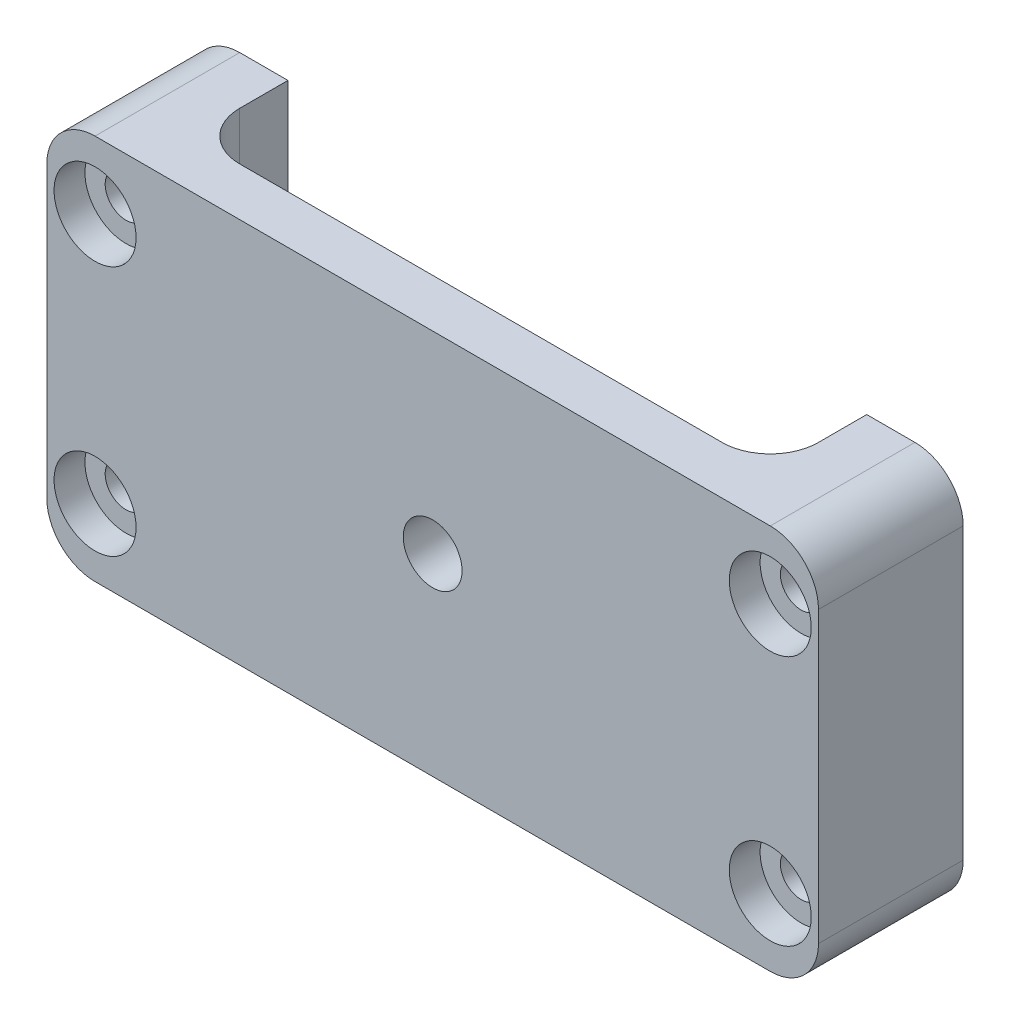
SolidWorks part; units mm, degrees
material "ABS"
ref_plane "Front Plane" through (0, 0, 0) normal (0, 0, 1) x (1, 0, 0)
ref_plane "Top Plane" through (0, 0, 0) normal (0, 1, 0) x (1, 0, 0)
ref_plane "Right Plane" through (0, 0, 0) normal (1, 0, 0) x (0, 0, -1)
sketch "Sketch1" plane through (0, 0, 0) normal (0, 0, 1) x (1, 0, 0)
  line L1 (0, 0) -> (40, 0)
  line L2 (0, 0) -> (0, 40)
  line L3 (0, 40) -> (40, 40)
  line L4 (40, 0) -> (40, 40)
  dimension "D1" = 40
  dimension "D2" = 40
extrude "Boss-Extrude1" add sketch "Sketch1" along normal blind 15
sketch "Sketch2" plane through (0, 0, 0) normal (0, -1, 0) x (1, 0, 0)
  line L1 (0, 0) -> (30, 0)
  line L2 (0, 0) -> (0, 10)
  line L3 (0, 10) -> (30, 10)
  line L4 (30, 0) -> (30, 10)
  dimension "D1" = 30
  dimension "D2" = 10
extrude "Cut-Extrude1" cut sketch "Sketch2" against normal through all
fillet "Fillet1" radius 5 1 edges at (30, 20, 10)
fillet "Fillet2" radius 5 2 edges at (40, 40, 7.5) (40, 0, 7.5)
hole_wizard "CBORE for M4 Pan Head Machine Screw1" positions "3DSketch1" profile "Sketch3" counterbore size "M4" standard "ANSI Metric" end condition through all
sketch3d "3DSketch1"
  line L1 (40, 5, 15) -> (40, 35, 15) construction
  point P0 (35, 33, 15)
  point P2 (35, 7, 15)
  dimension "D1" = 7
  dimension "D2" = 5
  dimension "D3" = 5
  dimension "D4" = 7
sketch "Sketch3" plane through (35, 33, 15) normal (1, 0, 0) x (0, -1, 0)
  line L0 (0, 0) -> (0, 15)
  line L1 (0, 15) -> (2.15, 15)
  line L3 (2.15, 15) -> (2.15, 3.2)
  line L4 (2.15, 3.2) -> (4.25, 3.2)
  line L5 (4.25, 3.2) -> (4.25, 0)
  line L7 (4.25, 0) -> (0, 0)
  line L11 (0, -6.35) -> (0, 107.95) construction
  dimension "Thru Hole Dia." = 4.3
  dimension "Thru Hole Depth" = 15
  dimension "C'Bore Dia." = 8.5
  dimension "C'Bore Depth" = 3.2
mirror "Mirror1" about plane through (0, 0, 15) normal (1, 0, 0) of "CBORE for M4 Pan Head Machine Screw1", "Fillet2", "Fillet1", "Cut-Extrude1", "Boss-Extrude1"
sketch "Sketch4" plane through (0, 0, 15) normal (0, 0, 1) x (1, 0, 0)
  circle A0 centre (0, 20) radius 3.048
  dimension "D1" = 6.096
extrude "Cut-Extrude2" cut sketch "Sketch4" against normal through all
